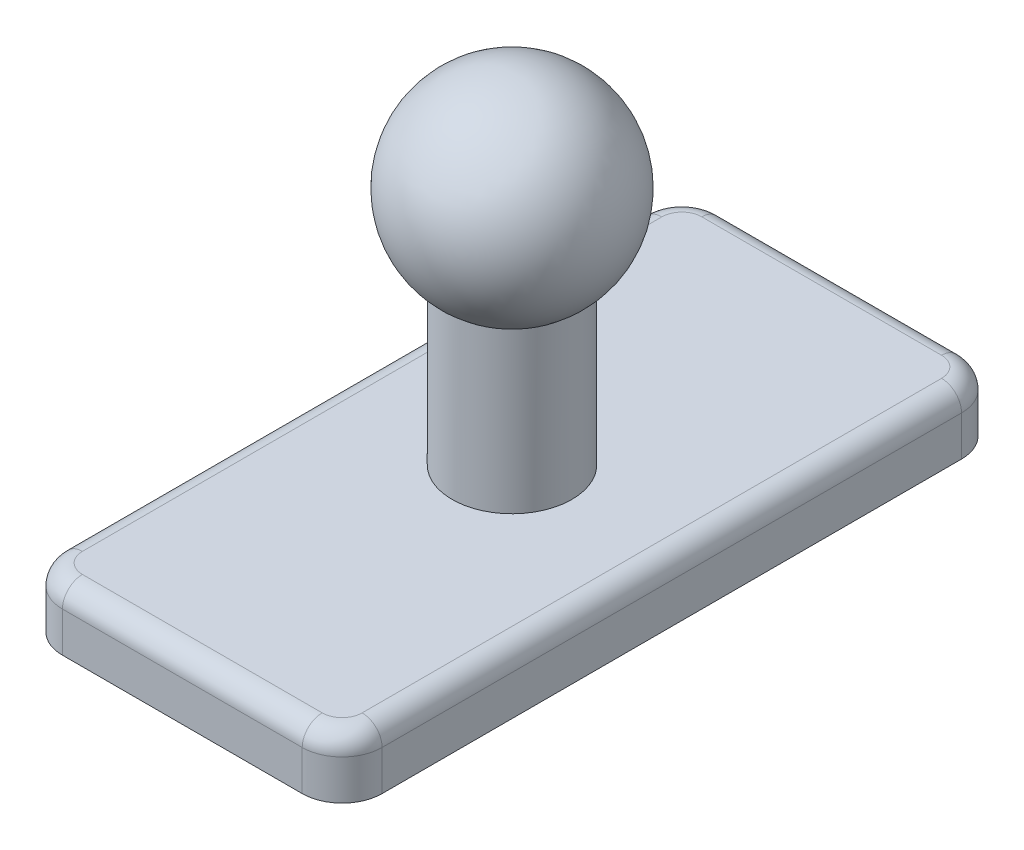
SolidWorks part; units mm, degrees
ref_plane "Front Plane" through (0, 0, 0) normal (0, 0, 1) x (1, 0, 0)
ref_plane "Top Plane" through (0, 0, 0) normal (0, 1, 0) x (1, 0, 0)
ref_plane "Right Plane" through (0, 0, 0) normal (1, 0, 0) x (0, 0, -1)
sketch "Sketch1" plane through (0, 0, 0) normal (0, 1, 0) x (1, 0, 0)
  line L1 (-13.285, -5.0784) -> (-1.285, -5.0784)
  line L2 (-15.285, -7.0784) -> (-15.285, -36.0784)
  line L3 (-13.285, -38.0784) -> (-1.285, -38.0784)
  line L4 (0.715, -7.0784) -> (0.715, -36.0784)
  arc A0 (-1.285, -5.0784) -> (0.715, -7.0784) centre (-1.285, -7.0784) cw
  arc A1 (-13.285, -5.0784) -> (-15.285, -7.0784) centre (-13.285, -7.0784) ccw
  arc A2 (-15.285, -36.0784) -> (-13.285, -38.0784) centre (-13.285, -36.0784) ccw
  arc A3 (-1.285, -38.0784) -> (0.715, -36.0784) centre (-1.285, -36.0784) ccw
  dimension "D3" = 2
  dimension "D1" = 16
  dimension "D2" = 33
extrude "Boss-Extrude1" add sketch "Sketch1" along normal blind 3
fillet "Fillet1" radius 1 8 edges at (-14.6992, 3, 5.6642) (-7.285, 3, 5.0784) (0.1292, 3, 5.6642) (0.715, 3, 21.5784) (0.1292, 3, 37.4926) (-7.285, 3, 38.0784) (-14.6992, 3, 37.4926) (-15.285, 3, 21.5784)
sketch "Sketch2" plane through (0, 3, 0) normal (0, 1, 0) x (1, 0, 0)
  line L0 (0.715, -7.0784) -> (0.715, -36.0784) construction
  line L1 (-1.285, -38.0784) -> (-13.285, -38.0784) construction
  circle A0 centre (-7.285, -21.5784) radius 3
  point P2 (0.715, -21.5784)
  point P5 (-7.285, -38.0784)
  dimension "D3" = 6
  dimension "D1" = 8
  dimension "D2" = 16.5
extrude "Boss-Extrude2" add sketch "Sketch2" along normal blind 12
sketch "Sketch3" plane through (0, 15, 0) normal (0, 1, 0) x (1, 0, 0)
  line L1 (-7.285, -12.7332) -> (-7.285, -32.415) construction
  circle A0 centre (-7.285, -21.5784) radius 5
  circle A1 centre (-7.285, -21.5784) radius 3 construction
  circle A2 centre (-7.285, -21.5784) radius 3 construction
  dimension "D1" = 2
revolve "Revolve9" add sketch "Sketch3" angle 360 about L1
